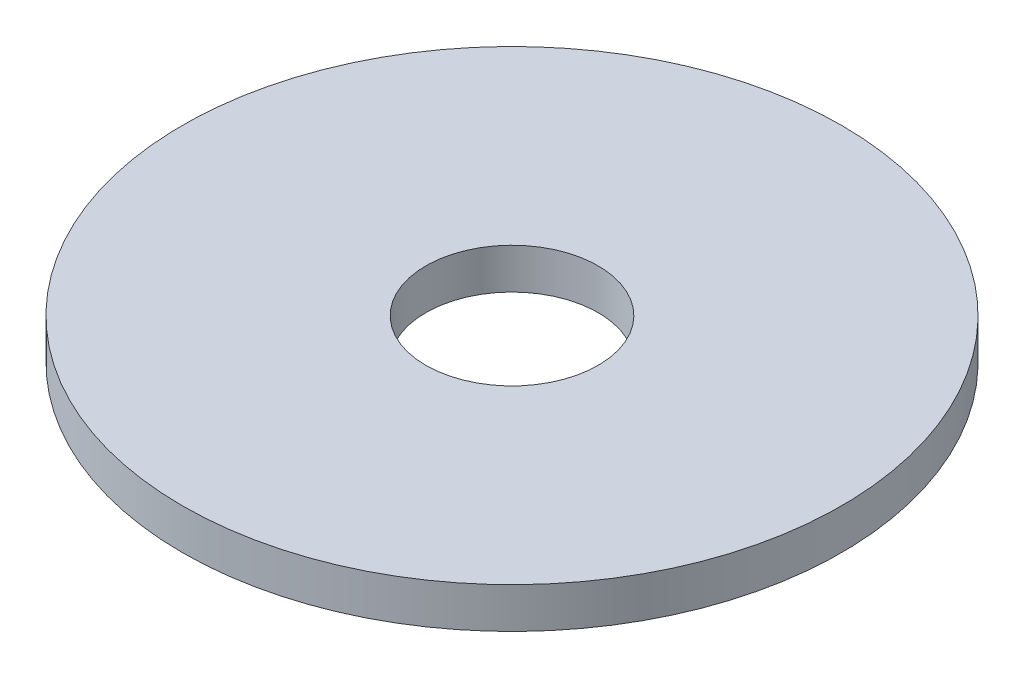
SolidWorks part; units mm, degrees
ref_plane "Front Plane" through (0, 0, 0) normal (0, 0, 1) x (1, 0, 0)
ref_plane "Top Plane" through (0, 0, 0) normal (0, 1, 0) x (1, 0, 0)
ref_plane "Right Plane" through (0, 0, 0) normal (1, 0, 0) x (0, 0, -1)
sketch "Sketch1" plane through (0, 0, 0) normal (0, 1, 0) x (1, 0, 0)
  circle A0 centre (0, 0) radius 8.125
extrude "Boss-Extrude1" add sketch "Sketch1" along normal blind 1
sketch "Sketch2" plane through (0, 1, 0) normal (0, 1, 0) x (1, 0, 0)
  circle A0 centre (0, 0) radius 2.125
extrude "Cut-Extrude1" cut sketch "Sketch2" against normal blind 1
